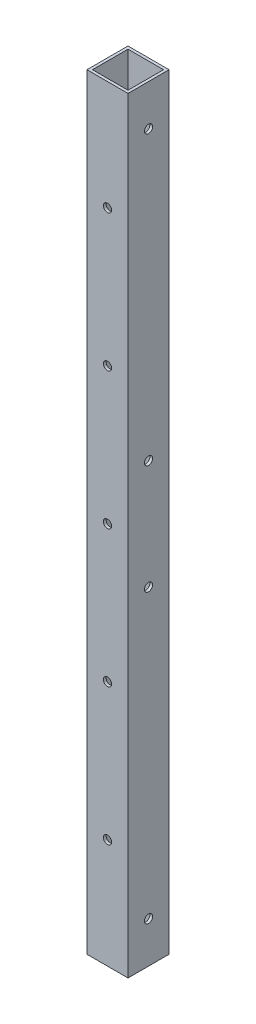
SolidWorks part; units mm, degrees
material "6061-O (SS)"
ref_plane "前视基准面" through (0, 0, 0) normal (0, 0, 1) x (1, 0, 0)
ref_plane "上视基准面" through (0, 0, 0) normal (0, 1, 0) x (1, 0, 0)
ref_plane "右视基准面" through (0, 0, 0) normal (1, 0, 0) x (0, 0, -1)
sketch "草图1" plane through (0, 0, 0) normal (0, 1, 0) x (1, 0, 0)
  line L0 (-6.5, 6.5) -> (6.5, 6.5)
  line L1 (-7.5, -7.5) -> (7.5, -7.5)
  line L2 (-7.5, -7.5) -> (-7.5, 7.5)
  line L3 (-7.5, 7.5) -> (7.5, 7.5)
  line L4 (7.5, -7.5) -> (7.5, 7.5)
  line L5 (-7.5, -7.5) -> (7.5, 7.5) construction
  line L6 (-7.5, 7.5) -> (7.5, -7.5) construction
  line L7 (6.5, -6.5) -> (6.5, 6.5)
  line L8 (-6.5, -6.5) -> (6.5, -6.5)
  line L9 (-6.5, -6.5) -> (-6.5, 6.5)
  point P0 (0, 0)
  dimension "D1" = 15
  dimension "D2" = 1
extrude "凸台-拉伸1" add sketch "草图1" along normal blind 280
sketch "草图2" plane through (0, 0, 7.5) normal (0, 0, 1) x (1, 0, 0)
  line L0 (0, 0) -> (0, 280) construction
  line L1 (-7.5, 280) -> (7.5, 280) construction
  line L2 (-7.5, 140) -> (7.5, 140) construction
  line L3 (-7.5, 280) -> (-7.5, 0) construction
  line L4 (7.5, 280) -> (7.5, 0) construction
  circle A0 centre (0, 40) radius 1.5
  circle A1 centre (0, 140) radius 1.5
  circle A2 centre (0, 90) radius 1.5
  circle A3 centre (0, 240) radius 1.5
  circle A4 centre (0, 190) radius 1.5
  dimension "D1" = 50
  dimension "D2" = 50
  dimension "D3" = 3
extrude "切除-拉伸1" cut sketch "草图2" against normal through all
sketch "草图3" plane through (7.5, 0, 0) normal (1, 0, 0) x (0, 0, -1)
  line L0 (0, 280) -> (0, 0) construction
  line L1 (-7.5, 280) -> (7.5, 280) construction
  line L2 (-7.5, 140) -> (7.5, 140) construction
  line L3 (-7.5, 280) -> (-7.5, 0) construction
  line L4 (7.5, 280) -> (7.5, 0) construction
  line L5 (-7.5, 0) -> (7.5, 0) construction
  circle A0 centre (0, 160) radius 1.5
  circle A1 centre (0, 120) radius 1.5
  circle A2 centre (0, 15) radius 1.5
  circle A3 centre (0, 265) radius 1.5
  dimension "D1" = 3
  dimension "D2" = 40
  dimension "D3" = 3
  dimension "D4" = 15
extrude "切除-拉伸2" cut sketch "草图3" against normal through all
